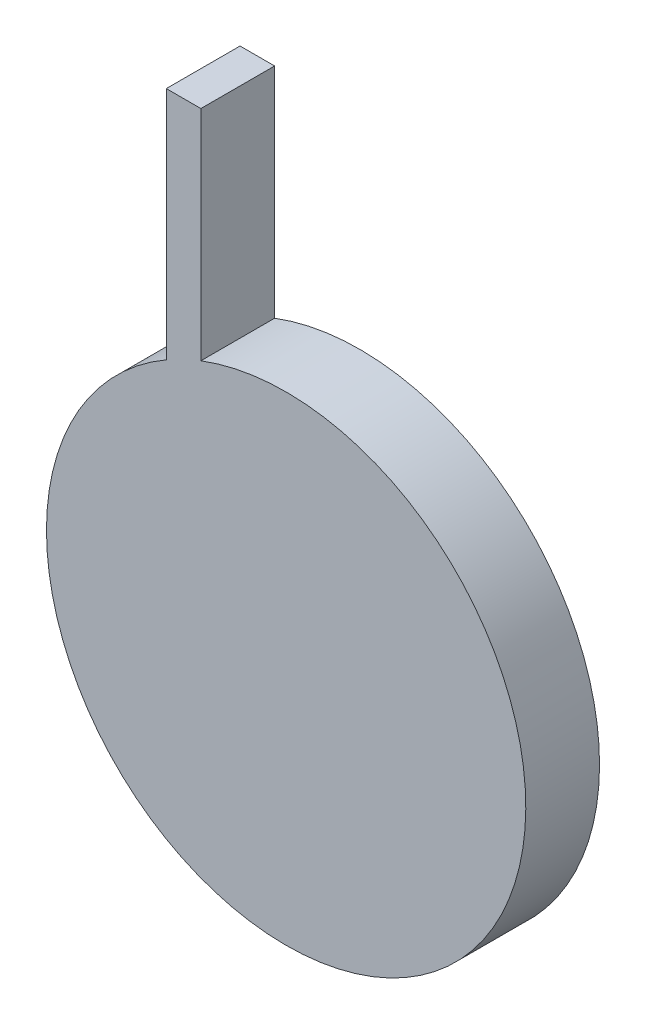
SolidWorks part; units mm, degrees
material "AISI Type A2 Tool Steel"
ref_plane "Front Plane" through (0, 0, 0) normal (0, 0, 1) x (1, 0, 0)
ref_plane "Top Plane" through (0, 0, 0) normal (0, 1, 0) x (1, 0, 0)
ref_plane "Right Plane" through (0, 0, 0) normal (1, 0, 0) x (0, 0, -1)
sketch "Sketch1" plane through (0, 0, 0) normal (0, 0, 1) x (1, 0, 0)
  circle A0 centre (0, 0) radius 26
  dimension "D1" = 52
extrude "PLATE" add sketch "Sketch1" along normal blind 8
sketch "Sketch2" plane through (0, 0, 0) normal (0, 0, 1) x (1, 0, 0)
  line L1 (-13, 20) -> (-9.25, 20)
  line L2 (-13, 20) -> (-13, 48)
  line L3 (-13, 48) -> (-9.25, 48)
  line L4 (-9.25, 20) -> (-9.25, 48)
  dimension "D1" = 3.75
  dimension "D2" = 13
  dimension "D3" = 20
  dimension "D4" = 48
extrude "DRIVE_LUG" add sketch "Sketch2" along normal blind 8
sketch "Sketch6" plane through (0, 0, 0) normal (0, 0, -1) x (-1, 0, 0)
  line L0 (13, 48) -> (13, 22.5167) construction
  line L1 (9.25, 48) -> (13, 48) construction
  circle A0 centre (11.25, 45.5) radius 1
  dimension "D1" = 1.75
  dimension "D3" = 2
  dimension "D2" = 2.5
extrude "Cut-Extrude5" cut sketch "Sketch6" against normal blind 4.5
